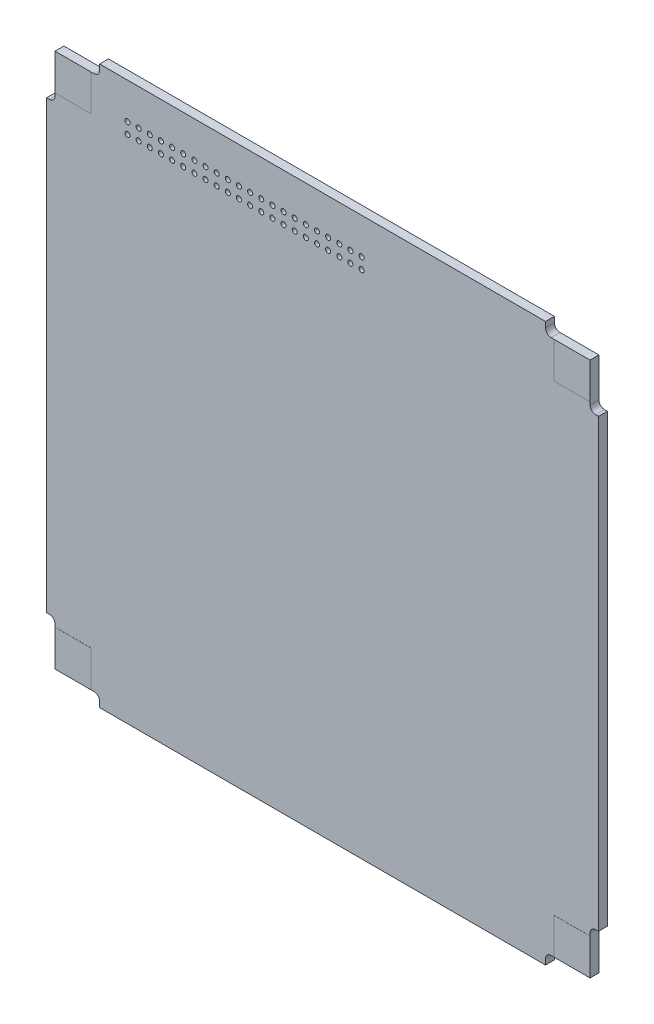
SolidWorks part; units mm, degrees
material "ABS"
ref_plane "Front Plane" through (0, 0, 0) normal (0, 0, 1) x (1, 0, 0)
ref_plane "Top Plane" through (0, 0, 0) normal (0, 1, 0) x (1, 0, 0)
ref_plane "Right Plane" through (0, 0, 0) normal (1, 0, 0) x (0, 0, -1)
sketch "Sketch1" plane through (0, 0, 0) normal (0, 0, 1) x (1, 0, 0)
  line L0 (-40, 50) -> (-40, 48)
  line L1 (-50, -50) -> (50, -50)
  line L2 (-50, -50) -> (-50, 50)
  line L3 (-50, 50) -> (50, 50)
  line L4 (50, -50) -> (50, 50)
  line L5 (-50, -50) -> (50, 50) construction
  line L6 (-50, 50) -> (50, -50) construction
  line L7 (-50, 50) -> (-40, 50)
  line L8 (-50, 50) -> (-50, 40)
  line L9 (-40, 48) -> (-48, 48)
  line L10 (-48, 48) -> (-48, 40)
  line L11 (50, 50) -> (40, 50)
  line L12 (50, 50) -> (50, 40)
  line L13 (-48, 40) -> (-50, 40)
  line L14 (50, 40) -> (48, 40)
  line L15 (-50, -50) -> (-37.8649, -50)
  line L16 (-50, -50) -> (-50, -37.8649)
  line L17 (50, 50) -> (50, 40)
  line L18 (50, 50) -> (40, 50)
  line L19 (50, -50) -> (41.5, -50)
  line L20 (50, -50) -> (50, -41.5)
  line L21 (48, 40) -> (48, 48)
  line L22 (48, 48) -> (40, 48)
  line L23 (40, 48) -> (40, 50)
  line L24 (40, -50) -> (40, -48)
  line L25 (50, -50) -> (40, -50)
  line L26 (50, -50) -> (50, -40)
  line L27 (40, -48) -> (48, -48)
  line L28 (48, -48) -> (48, -40)
  line L29 (48, -40) -> (50, -40)
  line L30 (-50, -40) -> (-48, -40)
  line L31 (-50, -50) -> (-50, -40)
  line L32 (-50, -50) -> (-40, -50)
  line L33 (-48, -40) -> (-48, -48)
  line L34 (-48, -48) -> (-40, -48)
  line L35 (-40, -48) -> (-40, -50)
  point P0 (0, 0)
  point P38 (0, 0)
  dimension "D1" = 100
  dimension "D2" = 100
  dimension "D3" = 2
  dimension "D4" = 10
  dimension "D5" = 4
extrude "Boss-Extrude1" add sketch "Sketch1" along normal blind 1.5875
fillet "Fillet1" radius 1 8 edges at (-48, -40, 0.7937) (-40, -48, 0.7937) (40, -48, 0.7937) (48, -40, 0.7937) (48, 40, 0.7937) (40, 48, 0.7937) (-40, 48, 0.7937) (-48, 40, 0.7937)
sketch "Sketch2" plane through (0, 0, 1.5875) normal (0, 0, 1) x (1, 0, 0)
  line L0 (0, 50) -> (0, -50) construction
  line L1 (-40, 50) -> (40, 50) construction
  line L2 (-40, -50) -> (40, -50) construction
  line L4 (-36, 45.8) -> (8, 45.8) construction
  line L5 (-36, 45.8) -> (-36, 43.55) construction
  line L6 (-36, 43.55) -> (8, 43.55) construction
  line L7 (8, 45.8) -> (8, 43.55) construction
  line L8 (-36, 50) -> (8, 50) construction
  line L9 (-36, 50) -> (-36, 45.8) construction
  line L10 (-36, 45.8) -> (8, 45.8) construction
  line L11 (8, 50) -> (8, 45.8) construction
  circle A0 centre (-35, 43.55) radius 0.45
  circle A1 centre (-33, 43.55) radius 0.45
  circle A2 centre (-31, 43.55) radius 0.45
  circle A3 centre (-29, 43.55) radius 0.45
  circle A4 centre (-27, 43.55) radius 0.45
  circle A5 centre (-25, 43.55) radius 0.45
  circle A6 centre (-23, 43.55) radius 0.45
  circle A7 centre (-21, 43.55) radius 0.45
  circle A8 centre (-19, 43.55) radius 0.45
  circle A9 centre (-17, 43.55) radius 0.45
  circle A10 centre (-15, 43.55) radius 0.45
  circle A11 centre (-13, 43.55) radius 0.45
  circle A12 centre (-11, 43.55) radius 0.45
  circle A13 centre (-9, 43.55) radius 0.45
  circle A14 centre (-7, 43.55) radius 0.45
  circle A15 centre (-5, 43.55) radius 0.45
  circle A16 centre (-3, 43.55) radius 0.45
  circle A17 centre (-1, 43.55) radius 0.45
  circle A18 centre (1, 43.55) radius 0.45
  circle A19 centre (3, 43.55) radius 0.45
  circle A20 centre (5, 43.55) radius 0.45
  circle A21 centre (7, 43.55) radius 0.45
  circle A22 centre (-33, 41.55) radius 0.45
  circle A23 centre (-31, 41.55) radius 0.45
  circle A24 centre (-29, 41.55) radius 0.45
  circle A25 centre (-27, 41.55) radius 0.45
  circle A26 centre (-25, 41.55) radius 0.45
  circle A27 centre (-23, 41.55) radius 0.45
  circle A28 centre (-21, 41.55) radius 0.45
  circle A29 centre (-19, 41.55) radius 0.45
  circle A30 centre (-17, 41.55) radius 0.45
  circle A31 centre (-15, 41.55) radius 0.45
  circle A32 centre (-13, 41.55) radius 0.45
  circle A33 centre (-11, 41.55) radius 0.45
  circle A34 centre (-9, 41.55) radius 0.45
  circle A35 centre (-7, 41.55) radius 0.45
  circle A36 centre (-5, 41.55) radius 0.45
  circle A37 centre (-3, 41.55) radius 0.45
  circle A38 centre (-1, 41.55) radius 0.45
  circle A39 centre (1, 41.55) radius 0.45
  circle A40 centre (3, 41.55) radius 0.45
  circle A41 centre (5, 41.55) radius 0.45
  circle A42 centre (7, 41.55) radius 0.45
  circle A43 centre (-35, 41.55) radius 0.45
  dimension "D1" = 0.9
  dimension "D6" = 15
  dimension "D4" = 42
  dimension "D5" = 2
  dimension "D7" = 2.25
  dimension "D8" = 44
  dimension "D10" = 1
  dimension "D11" = 4.2
  dimension "D2" = 22
  dimension "D3" = 2
extrude "Cut-Extrude1" cut sketch "Sketch2" against normal through all
sketch "Sketch4" plane through (0, 0, 1.5875) normal (0, 0, 1) x (1, 0, 0)
  line L1 (-48, 48) -> (-41.5, 48)
  line L2 (-48, 48) -> (-48, 41.5)
  line L3 (-48, 41.5) -> (-41.5, 41.5)
  line L4 (-41.5, 48) -> (-41.5, 41.5)
  line L5 (-48, -48) -> (-41.5, -48)
  line L6 (-48, -48) -> (-48, -41.5)
  line L7 (-48, -41.5) -> (-41.5, -41.5)
  line L8 (-41.5, -48) -> (-41.5, -41.5)
  line L9 (48, -48) -> (41.5, -48)
  line L10 (48, -48) -> (48, -41.5)
  line L11 (48, -41.5) -> (41.5, -41.5)
  line L12 (41.5, -48) -> (41.5, -41.5)
  line L13 (48, 48) -> (41.5, 48)
  line L14 (48, 48) -> (48, 41.5)
  line L15 (48, 41.5) -> (41.5, 41.5)
  line L16 (41.5, 48) -> (41.5, 41.5)
  dimension "D1" = 6.5
extrude "Boss-Extrude2" add sketch "Sketch4" along normal blind 0.01
sketch "Sketch5" plane through (0, 0, 0) normal (0, 0, -1) x (-1, 0, 0)
  line L0 (40, -50) -> (-40, -50) construction
  line L1 (-49.5, 50) -> (49.5, 50)
  line L2 (-49.5, 50) -> (-49.5, -50)
  line L3 (-49.5, -50) -> (49.5, -50)
  line L4 (49.5, 50) -> (49.5, -50)
  line L5 (40, 50) -> (-40, 50) construction
  line L6 (50, -40) -> (50, 40) construction
  dimension "D1" = 99
  dimension "D2" = 0.5
extrude "Cut-Extrude3" cut sketch "Sketch5" against normal through all flip side to cut
